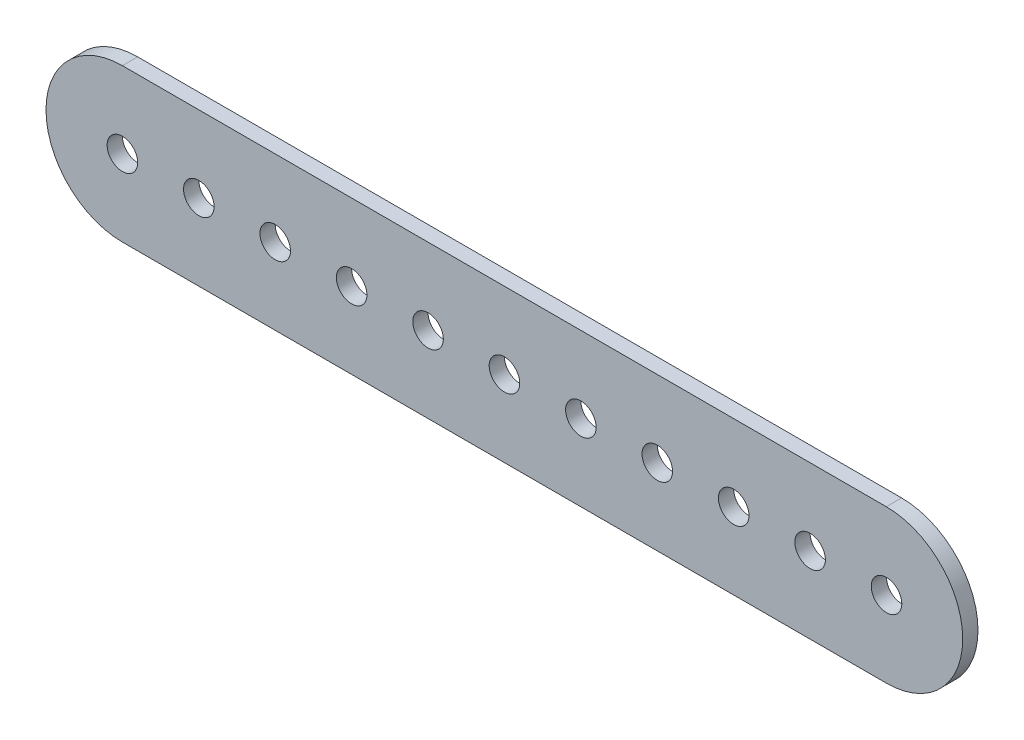
SolidWorks part; units mm, degrees
ref_plane "Front Plane" through (0, 0, 0) normal (0, 0, 1) x (1, 0, 0)
ref_plane "Top Plane" through (0, 0, 0) normal (0, 1, 0) x (1, 0, 0)
ref_plane "Right Plane" through (0, 0, 0) normal (1, 0, 0) x (0, 0, -1)
sketch "Sketch2" plane through (0, 0, 0) normal (0, 0, 1) x (1, 0, 0)
  line L0 (0, 0) -> (5000, 0) construction
  line L1 (0, 500) -> (5000, 500)
  line L2 (0, -500) -> (5000, -500)
  arc A0 (0, 500) -> (0, -500) centre (0, 0) ccw
  arc A1 (5000, -500) -> (5000, 500) centre (5000, 0) ccw
  circle A2 centre (0, 0) radius 100
  circle A3 centre (500.126, 0) radius 100
  circle A4 centre (1000.252, 0) radius 100
  circle A5 centre (1500.378, 0) radius 100
  circle A6 centre (2000.504, 0) radius 100
  circle A7 centre (2500.63, 0) radius 100
  circle A8 centre (3000.756, 0) radius 100
  circle A9 centre (3500.882, 0) radius 100
  circle A10 centre (4001.008, 0) radius 100
  circle A11 centre (4501.134, 0) radius 100
  circle A12 centre (5001.26, 0) radius 100
  point P3 (2500, 0)
  dimension "D1" = 11
extrude "Boss-Extrude2" add sketch "Sketch2" along normal blind 100
